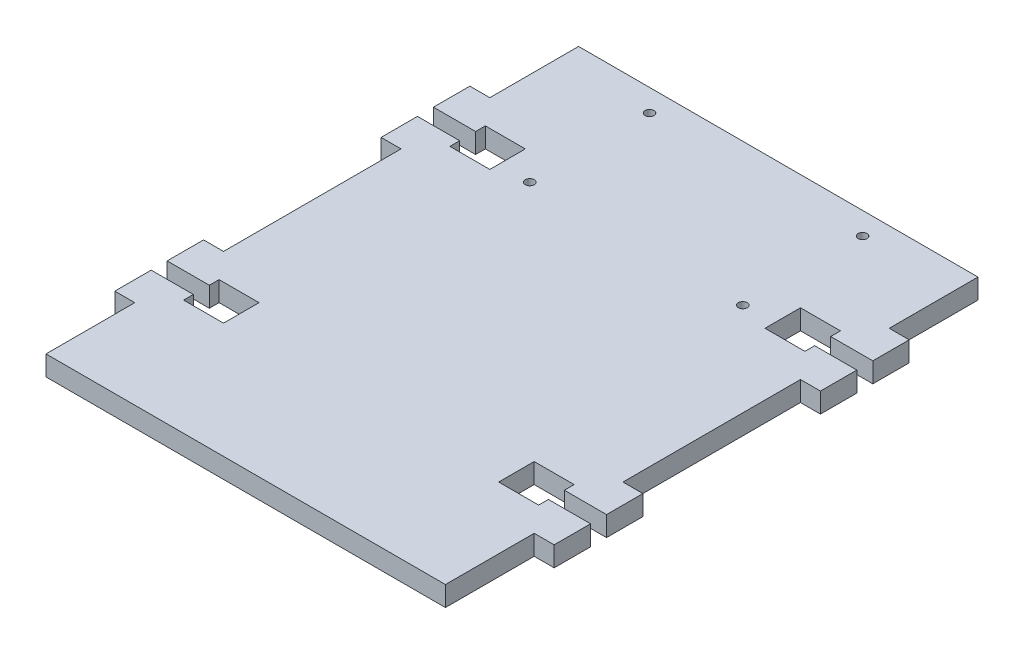
SolidWorks part; units mm, degrees
material "Oak"
ref_plane "Front Plane" through (0, 0, 0) normal (0, 0, 1) x (1, 0, 0)
ref_plane "Top Plane" through (0, 0, 0) normal (0, 1, 0) x (1, 0, 0)
ref_plane "Right Plane" through (0, 0, 0) normal (1, 0, 0) x (0, 0, -1)
sketch "Sketch1" plane through (0, 0, 0) normal (0, 1, 0) x (1, 0, 0)
  line L0 (49.5, 40) -> (-49.5, 20) construction
  line L1 (-45, -60) -> (45, -60)
  line L2 (-45, -60) -> (-45, 60)
  line L3 (-45, 60) -> (45, 60)
  line L4 (45, -60) -> (45, 60)
  line L5 (-45, -60) -> (45, 60) construction
  line L6 (-45, 60) -> (45, -60) construction
  line L7 (-49.5, -40) -> (49.5, -40)
  line L8 (-49.5, -40) -> (-49.5, 40)
  line L9 (-49.5, 40) -> (49.5, 40)
  line L10 (49.5, -40) -> (49.5, 40)
  line L11 (-49.5, -40) -> (49.5, 40) construction
  line L12 (-49.5, 40) -> (49.5, -40) construction
  line L13 (-49.5, -20) -> (49.5, -20)
  line L14 (-49.5, -20) -> (-49.5, 20)
  line L15 (-49.5, 20) -> (49.5, 20)
  line L16 (49.5, -20) -> (49.5, 20)
  line L17 (-49.5, -20) -> (49.5, 20) construction
  line L18 (-49.5, 20) -> (49.5, -20) construction
  line L19 (-49.5, -20) -> (49.5, -40) construction
  line L21 (49.5, 28.2) -> (-49.5, 28.2)
  line L22 (49.5, 28.2) -> (49.5, 31.8)
  line L23 (49.5, 31.8) -> (-49.5, 31.8)
  line L24 (-49.5, 28.2) -> (-49.5, 31.8)
  line L25 (49.5, 28.2) -> (-49.5, 31.8) construction
  line L26 (49.5, 31.8) -> (-49.5, 28.2) construction
  line L27 (49.5, -31.8) -> (-49.5, -31.8)
  line L28 (49.5, -31.8) -> (49.5, -28.2)
  line L29 (49.5, -28.2) -> (-49.5, -28.2)
  line L30 (-49.5, -31.8) -> (-49.5, -28.2)
  line L31 (49.5, -31.8) -> (-49.5, -28.2) construction
  line L32 (49.5, -28.2) -> (-49.5, -31.8) construction
  line L33 (35.5, 28.2) -> (-35.5, 28.2)
  line L34 (35.5, 28.2) -> (35.5, 31.8)
  line L35 (35.5, 31.8) -> (-35.5, 31.8)
  line L36 (-35.5, 28.2) -> (-35.5, 31.8)
  line L37 (35.5, 28.2) -> (-35.5, 31.8) construction
  line L38 (35.5, 31.8) -> (-35.5, 28.2) construction
  line L39 (35.5, -31.8) -> (-35.5, -31.8)
  line L40 (35.5, -31.8) -> (35.5, -28.2)
  line L41 (35.5, -28.2) -> (-35.5, -28.2)
  line L42 (-35.5, -31.8) -> (-35.5, -28.2)
  line L43 (35.5, -31.8) -> (-35.5, -28.2) construction
  line L44 (35.5, -28.2) -> (-35.5, -31.8) construction
  line L45 (-31, 26) -> (-40, 26)
  line L46 (-31, 26) -> (-31, 34)
  line L47 (-31, 34) -> (-40, 34)
  line L48 (-40, 26) -> (-40, 34)
  line L49 (-31, 26) -> (-40, 34) construction
  line L50 (-31, 34) -> (-40, 26) construction
  line L51 (31, 26) -> (40, 26)
  line L52 (31, 26) -> (31, 34)
  line L53 (31, 34) -> (40, 34)
  line L54 (40, 26) -> (40, 34)
  line L55 (31, 26) -> (40, 34) construction
  line L56 (31, 34) -> (40, 26) construction
  line L57 (-31, -34) -> (-40, -34)
  line L58 (-31, -34) -> (-31, -26)
  line L59 (-31, -26) -> (-40, -26)
  line L60 (-40, -34) -> (-40, -26)
  line L61 (-31, -34) -> (-40, -26) construction
  line L62 (-31, -26) -> (-40, -34) construction
  line L63 (31, -34) -> (40, -34)
  line L64 (31, -34) -> (31, -26)
  line L65 (31, -26) -> (40, -26)
  line L66 (40, -34) -> (40, -26)
  line L67 (31, -34) -> (40, -26) construction
  line L68 (31, -26) -> (40, -34) construction
  point P0 (0, 0)
  point P6 (0, 0)
  point P11 (0, 0)
  point P16 (0, 30)
  point P21 (0, -30)
  point P26 (0, 30)
  point P31 (0, -30)
  point P36 (-35.5, 30)
  point P41 (35.5, 30)
  point P46 (-35.5, -30)
  point P51 (35.5, -30)
  dimension "D1" = 20
  dimension "D2" = 20
  dimension "D3" = 90
  dimension "D4" = 99
  dimension "D5" = 40
  dimension "D6" = 3.6
  dimension "D7" = 3.6
  dimension "D8" = 14
  dimension "D9" = 14
  dimension "D10" = 9
  dimension "D11" = 8
  dimension "D12" = 8
  dimension "D13" = 9
  dimension "D14" = 8
  dimension "D15" = 9
  dimension "D16" = 8
  dimension "D17" = 9
extrude "Boss-Extrude1" add sketch "Sketch1" along normal blind 4.5 contours L2 L9 L4 L3 | L54 L23 L4 L9 L2 L48 L47 L46 L35 L52 L53 | L23 L2 L9 L8 | L2 L21 L8 L15 | L54 L51 L52 L33 L46 L45 L48 L21 L2 L15 L4 | L33 L52 L35 L46 | L15 L2 L13 L4 | L66 L29 L4 L13 L2 L60 L59 L58 L41 L64 L65 | L29 L2 L13 L8 | L2 L27 L8 L7 | L66 L63 L64 L39 L58 L57 L60 L27 L2 L7 L4 | L39 L64 L41 L58 | L29 L10 L13 L4 | L10 L27 L4 L7 | L10 L21 L4 L15 | L23 L10 L9 L4 | L7 L2 L1 L4
sketch "Sketch2" plane through (0, 4.5, 0) normal (0, 1, 0) x (1, 0, 0)
  line L0 (-45, 60) -> (45, 60) construction
  line L1 (-24, 28) -> (24, 28)
  line L2 (-24, 28) -> (-24, 55)
  line L3 (-24, 55) -> (24, 55)
  line L4 (24, 28) -> (24, 55)
  circle A0 centre (-24, 55) radius 1
  circle A1 centre (24, 55) radius 1
  circle A2 centre (24, 28) radius 1
  circle A3 centre (-24, 28) radius 1
  dimension "D5" = 2
  dimension "D6" = 2
  dimension "D7" = 2
  dimension "D8" = 2
  dimension "D1" = 24
  dimension "D2" = 48
  dimension "D3" = 27
  dimension "D4" = 5
extrude "Cut-Extrude1" cut sketch "Sketch2" against normal blind 10 contours L3 A0 L2 | L2 A0 L3 | L4 A1 L3 | L3 A1 L4 | L1 A2 L4 | L4 A2 L1 | L1 A3 L2 | L2 A3 L1
